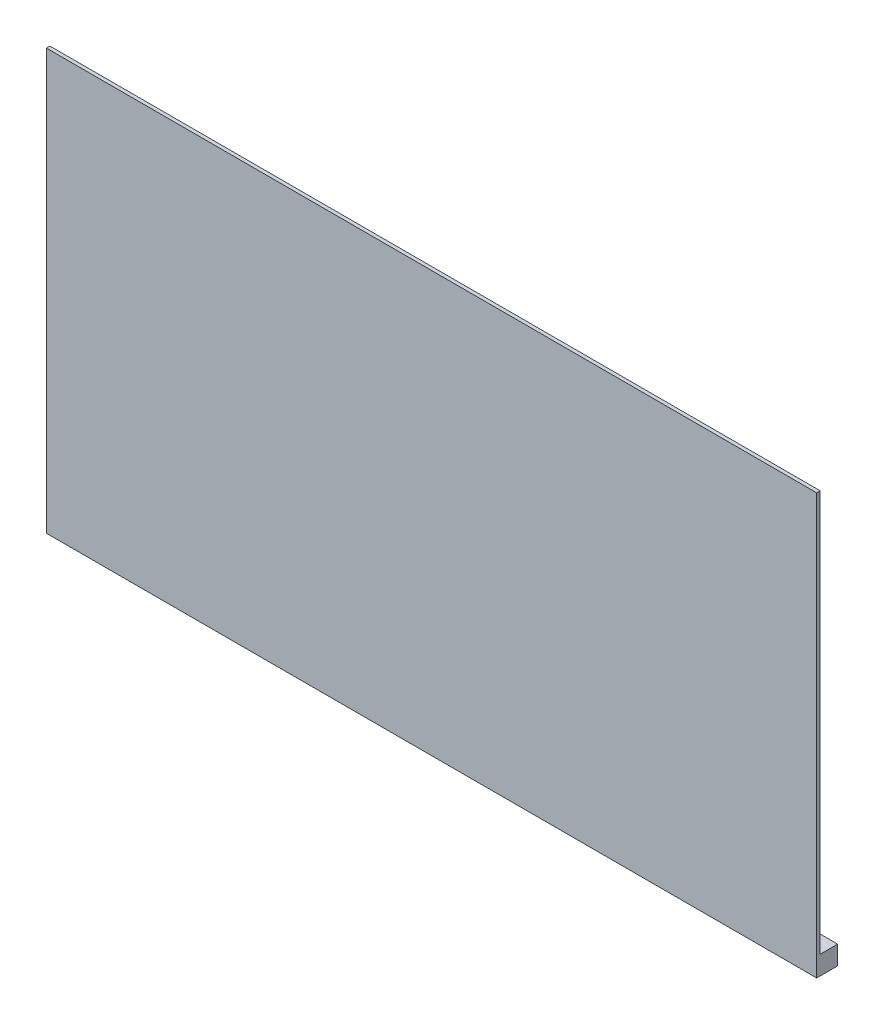
SolidWorks part; units mm, degrees
ref_plane "Спереди" through (0, 0, 0) normal (0, 0, 1) x (1, 0, 0)
ref_plane "Сверху" through (0, 0, 0) normal (0, 1, 0) x (1, 0, 0)
ref_plane "Справа" through (0, 0, 0) normal (1, 0, 0) x (0, 0, -1)
other "Configuration Table"
sketch "Эскиз1" plane through (0, 0, 0) normal (0, 0, 1) x (1, 0, 0)
  line L1 (4400, -6600) -> (8800, -6600)
  line L2 (4400, -6600) -> (4400, -9000)
  line L3 (4400, -9000) -> (8800, -9000)
  line L4 (8800, -6600) -> (8800, -9000)
  point P4 (4400, -9000)
  point P6 (0, 0)
  point P7 (4400.4727, -6603.4419)
  point P11 (8800, -8986.7941)
  point P14 (4400, -6600)
  point P16 (4400, -9000)
extrude "Бобышка-Вытянуть1" add sketch "Эскиз1" along normal mid plane 20 contours L3 L4 L1 L2
sketch "Эскиз2" plane through (0, 0, -10) normal (0, 0, -1) x (-1, 0, 0)
  line L0 (-8800, -6600) -> (-8800, -9000) construction
  line L1 (-4400, -9000) -> (-8800, -9000)
  line L2 (-4400, -9000) -> (-4400, -8892.3319)
  line L3 (-4400, -8892.3319) -> (-8800, -8892.3319)
  line L4 (-8800, -9000) -> (-8800, -8892.3319)
  point P5 (-5627.2263, -8962.6948)
  point P6 (-8800, -8892.3319)
extrude "Бобышка-Вытянуть2" add sketch "Эскиз2" along normal blind 100
